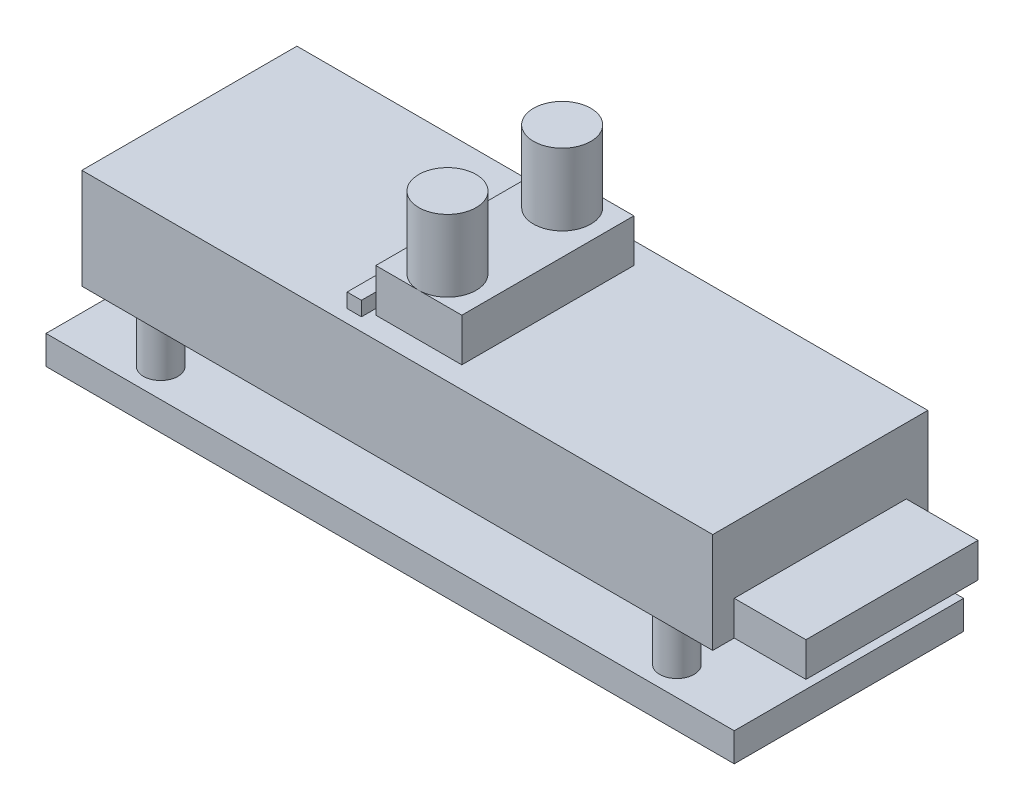
SolidWorks part; units mm, degrees
ref_plane "Front Plane" through (0, 0, 0) normal (0, 0, 1) x (1, 0, 0)
ref_plane "Top Plane" through (0, 0, 0) normal (0, 1, 0) x (1, 0, 0)
ref_plane "Right Plane" through (0, 0, 0) normal (1, 0, 0) x (0, 0, -1)
other "Configuration Table"
sketch "Sketch1" plane through (0, 0, 0) normal (0, 1, 0) x (1, 0, 0)
  line L1 (-1200, -400) -> (1200, -400)
  line L2 (-1200, -400) -> (-1200, 400)
  line L3 (-1200, 400) -> (1200, 400)
  line L4 (1200, -400) -> (1200, 400)
extrude "Boss-Extrude1" add sketch "Sketch1" along normal blind 100
sketch "Sketch2" plane through (0, 0, 0) normal (0, 1, 0) x (1, 0, 0)
  circle A0 centre (-900, -300) radius 60
extrude "Boss-Extrude2" add sketch "Sketch2" along normal blind 180 from offset 100
sketch "Sketch3" plane through (0, 0, 0) normal (0, 1, 0) x (1, 0, 0)
  circle A0 centre (-900, 300) radius 60
extrude "Boss-Extrude3" add sketch "Sketch3" along normal blind 180 from offset 100
sketch "Sketch4" plane through (0, 0, 0) normal (0, 1, 0) x (1, 0, 0)
  circle A0 centre (900, -300) radius 60
extrude "Boss-Extrude4" add sketch "Sketch4" along normal blind 180 from offset 100
sketch "Sketch5" plane through (0, 0, 0) normal (0, 1, 0) x (1, 0, 0)
  circle A0 centre (900, 300) radius 60
extrude "Boss-Extrude5" add sketch "Sketch5" along normal blind 180 from offset 100
sketch "Sketch6" plane through (0, 0, 0) normal (0, 1, 0) x (1, 0, 0)
  line L1 (-1100, -375) -> (1100, -375)
  line L2 (-1100, -375) -> (-1100, 375)
  line L3 (-1100, 375) -> (1100, 375)
  line L4 (1100, -375) -> (1100, 375)
extrude "Boss-Extrude6" add sketch "Sketch6" along normal blind 350 from offset 280
sketch "Sketch7" plane through (0, 0, 0) normal (0, 1, 0) x (1, 0, 0)
  line L0 (1100, -375) -> (1100, 375) construction
  line L1 (1100, -300) -> (1350, -300)
  line L2 (1100, -300) -> (1100, 300)
  line L3 (1100, 300) -> (1350, 300)
  line L4 (1350, -300) -> (1350, 300)
extrude "Boss-Extrude7" add sketch "Sketch7" along normal blind 120 from offset 280
sketch "Sketch8" plane through (0, 0, 0) normal (0, 1, 0) x (1, 0, 0)
  line L1 (-200, -350) -> (-150, -350)
  line L2 (-200, -350) -> (-200, 350)
  line L3 (-200, 350) -> (-150, 350)
  line L4 (-150, -350) -> (-150, 350)
extrude "Boss-Extrude8" add sketch "Sketch8" along normal blind 50 from offset 650
sketch "Sketch9" plane through (0, 0, 0) normal (0, 1, 0) x (1, 0, 0)
  line L0 (-150, -350) -> (-150, 350) construction
  line L1 (-150, -300) -> (150, -300)
  line L2 (-150, -300) -> (-150, 300)
  line L3 (-150, 300) -> (150, 300)
  line L4 (150, -300) -> (150, 300)
extrude "Boss-Extrude9" add sketch "Sketch9" along normal blind 150 from offset 630
sketch "Sketch10" plane through (0, 0, 0) normal (0, 1, 0) x (1, 0, 0)
  circle A0 centre (0, -200) radius 100
extrude "Boss-Extrude10" add sketch "Sketch10" along normal blind 250 from offset 780
sketch "Sketch11" plane through (0, 0, 0) normal (0, 1, 0) x (1, 0, 0)
  circle A0 centre (0, 200) radius 100
extrude "Boss-Extrude11" add sketch "Sketch11" along normal blind 250 from offset 780
sketch "Sketch12" plane through (0, 0, 0) normal (0, 1, 0) x (1, 0, 0)
  circle A0 centre (0, 0) radius 55
extrude "Boss-Extrude12" add sketch "Sketch12" along normal blind 180 from offset 280 flip side to cut
